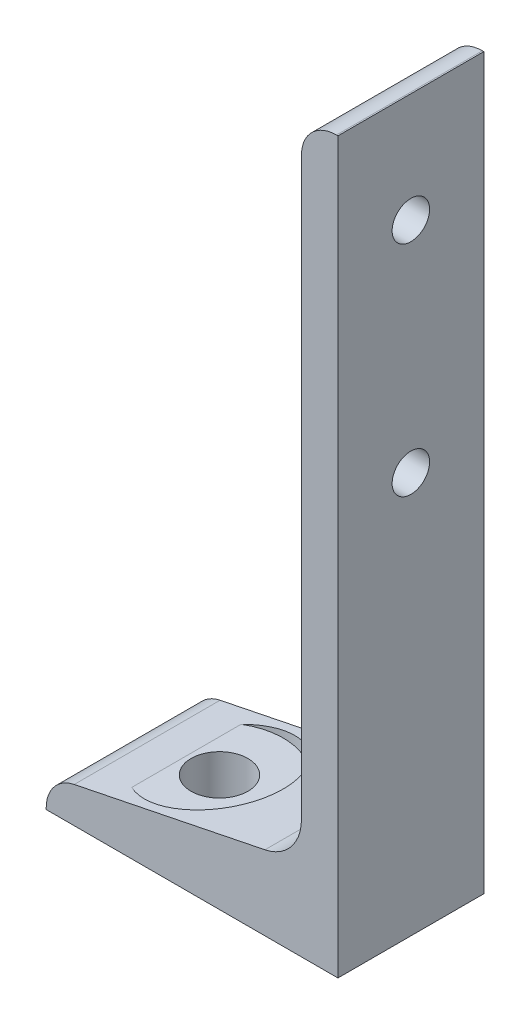
SolidWorks part; units mm, degrees
ref_plane "Front Plane" through (0, 0, 0) normal (0, 0, 1) x (1, 0, 0)
ref_plane "Top Plane" through (0, 0, 0) normal (0, 1, 0) x (1, 0, 0)
ref_plane "Right Plane" through (0, 0, 0) normal (1, 0, 0) x (0, 0, -1)
sketch "Sketch1" plane through (0, 0, 0) normal (0, 0, 1) x (1, 0, 0)
  line L0 (0, 127) -> (0, 0)
  line L1 (0, 0) -> (-50.8, 0)
  line L2 (-50.8, 0) -> (-50.8, 0.254)
  line L3 (-45.9189, 6.2277) -> (-12.7056, 12.9823)
  line L4 (-6.35, 20.7605) -> (-6.35, 120.904)
  line L5 (-0.254, 127) -> (0, 127)
  arc A0 (-50.8, 0.254) -> (-45.9189, 6.2277) centre (-44.704, 0.254) cw
  arc A1 (-6.35, 120.904) -> (-0.254, 127) centre (-0.254, 120.904) cw
  arc A2 (-12.7056, 12.9823) -> (-6.35, 20.7605) centre (-14.2875, 20.7605) ccw
  point P11 (-6.35, 127)
  point P14 (-6.35, 14.2748)
  dimension "D1" = 6.096
  dimension "D3" = 7.9375
  dimension "A" = 127
  dimension "D2" = 14.2748
  dimension "F" = 50.8
  dimension "E" = 6.35
extrude "Extrude1" add sketch "Sketch1" along normal mid plane 25.4
sketch "Sketch2" plane through (0, 0, 0) normal (1, 0, 0) x (0, 0, -1)
  line L0 (0, 0) -> (0, 69.85) construction
  line L1 (0, 69.85) -> (0, 107.95) construction
  line L2 (-12.7, 127) -> (12.7, 127) construction
  circle A0 centre (0, 69.85) radius 3.2639
  circle A1 centre (0, 107.95) radius 3.2639
  dimension "D1" = 15.7861
  dimension "K" = 6.5278
  dimension "B" = 69.85
  dimension "C" = 38.1
sketch "Sketch3" plane through (0, 0, 0) normal (0, 1, 0) x (1, 0, 0)
  line L0 (-50.8, 0) -> (-33.3248, 0) construction
  line L1 (-50.8, -12.7) -> (-50.8, 12.7) construction
  circle A0 centre (-33.3248, 0) radius 4.953
  dimension "L" = 9.906
  dimension "D1" = 17.4752
ref_plane "Plane1" through (0, 7.62, 0) normal (0, 1, 0) x (-1, 0, 0)
sketch "Sketch4" plane through (0, 7.62, 0) normal (0, 1, 0) x (-1, 0, 0)
  line L0 (33.3248, 11.1125) -> (50.8, 11.1125)
  line L1 (33.3248, -11.1125) -> (50.8, -11.1125)
  line L2 (50.8, 12.7) -> (50.8, -12.7) construction
  line L3 (50.8, 11.1125) -> (50.8, -11.1125)
  arc A0 (33.3248, 11.1125) -> (33.3248, -11.1125) centre (33.3248, 0) ccw
  arc A1 (33.3248, 11.1125) -> (33.3248, -11.1125) centre (33.3248, 0) cw construction
  dimension "M" = 22.225
sketch "Sketch5" plane through (-6.35, 0, 0) normal (-1, 0, 0) x (0, 0, 1)
  circle A0 centre (0, 69.85) radius 3.2639 construction
  circle A1 centre (0, 107.95) radius 3.2639 construction
  circle A2 centre (0, 69.85) radius 3.2639
  circle A3 centre (0, 107.95) radius 3.2639
extrude "Cut-Extrude1" cut sketch "Sketch5" against normal through all
sketch "Sketch6" plane through (0, 7.62, 0) normal (0, 1, 0) x (-1, 0, 0)
  circle A0 centre (33.3248, 0) radius 4.953 construction
  circle A1 centre (33.3248, 0) radius 4.953
extrude "Cut-Extrude2" cut sketch "Sketch6" against normal through all
sketch "Sketch7" plane through (0, 7.62, 0) normal (0, 1, 0) x (-1, 0, 0)
  line L0 (33.3248, 0) -> (33.3248, 11.1125) construction
  line L3 (50.8, 11.1125) -> (33.3248, 11.1125)
  line L4 (50.8, 11.1125) -> (33.3248, 11.1125) construction
  line L5 (50.8, -11.1125) -> (50.8, 11.1125)
  line L6 (50.8, -11.1125) -> (50.8, 11.1125) construction
  line L7 (33.3248, -11.1125) -> (50.8, -11.1125)
  line L8 (33.3248, -11.1125) -> (50.8, -11.1125) construction
  arc A1 (33.3248, 11.1125) -> (33.3248, -11.1125) centre (33.3248, 0) ccw
  circle A2 centre (33.3248, 0) radius 11.1125
  dimension "D1" = 0
extrude "Cut-Extrude3" cut sketch "Sketch7" along normal through all
sketch "Sketch9" plane through (-6.35, 0, 0) normal (-1, 0, 0) x (0, 0, 1)
  line L0 (-6.35, 107.95) -> (6.35, 107.95) construction
  circle A0 centre (6.35, 107.95) radius 3.2639
  circle A1 centre (6.35, 69.85) radius 3.2639
  circle A2 centre (-6.35, 69.85) radius 3.2639
  circle A3 centre (-6.35, 107.95) radius 3.2639
  circle A4 centre (0, 69.85) radius 3.2639 construction
  dimension "D1" = 12.7
sketch "Sketch10" plane through (0, 0, 0) normal (0, 1, 0) x (1, 0, 0)
  line L0 (-33.3248, -6.35) -> (-33.3248, 6.35) construction
  line L1 (-50.8, -11.1125) -> (-50.8, 11.1125) construction
  line L2 (-50.8, 17.4625) -> (-33.3248, 17.4625)
  line L3 (-50.8, 17.4625) -> (-50.8, -4.7625)
  line L4 (-50.8, -4.7625) -> (-33.3248, -4.7625)
  line L6 (-50.8, 4.7625) -> (-33.3248, 4.7625)
  line L7 (-50.8, 4.7625) -> (-50.8, -17.4625)
  line L8 (-50.8, -17.4625) -> (-33.3248, -17.4625)
  circle A0 centre (-33.3248, 6.35) radius 4.953
  circle A1 centre (-33.3248, -6.35) radius 4.953
  circle A2 centre (-33.3248, 0) radius 4.953 construction
  arc A3 (-33.3248, -4.7625) -> (-33.3248, 17.4625) centre (-33.3248, 6.35) ccw
  arc A4 (-33.3248, -17.4625) -> (-33.3248, 4.7625) centre (-33.3248, -6.35) ccw
  dimension "D1" = 12.7
sketch "Sketch11" [suppressed] plane through (0, 6.858, 0) normal (0, 1, 0) x (-1, 0, 0)
  line L3 (33.3248, -33.3375) -> (50.8, -33.3375)
  line L4 (50.8, -4.7625) -> (33.3248, -4.7625)
  line L5 (50.8, -33.3375) -> (50.8, -4.7625)
  line L6 (33.3248, -33.3375) -> (50.8, -33.3375)
  line L7 (50.8, -4.7625) -> (33.3248, -4.7625)
  line L8 (50.8, -33.3375) -> (50.8, -4.7625)
  line L9 (33.3248, 4.7625) -> (50.8, 4.7625)
  line L10 (50.8, 4.7625) -> (50.8, 33.3375)
  line L11 (50.8, 33.3375) -> (33.3248, 33.3375)
  line L12 (33.3248, 4.7625) -> (50.8, 4.7625)
  line L13 (50.8, 4.7625) -> (50.8, 33.3375)
  line L14 (50.8, 33.3375) -> (33.3248, 33.3375)
  arc A5 (33.3248, -4.7625) -> (33.3248, -33.3375) centre (33.3248, -19.05) ccw
  arc A6 (33.3248, -4.7625) -> (33.3248, -33.3375) centre (33.3248, -19.05) ccw
  arc A7 (33.3248, 33.3375) -> (33.3248, 4.7625) centre (33.3248, 19.05) ccw
  arc A8 (33.3248, 33.3375) -> (33.3248, 4.7625) centre (33.3248, 19.05) ccw
  dimension "D3" = 0
  dimension "D4" = 0
extrude "Cut-Extrude4" [suppressed] cut sketch "Sketch11" along normal through all
sketch "Sketch12" [suppressed] plane through (0, 6.858, 0) normal (0, 1, 0) x (-1, 0, 0)
  circle A0 centre (33.3248, 19.05) radius 6.7437 construction
  circle A1 centre (33.3248, -19.05) radius 6.7437 construction
  circle A2 centre (33.3248, 19.05) radius 6.7437
  circle A3 centre (33.3248, -19.05) radius 6.7437
extrude "Cut-Extrude5" [suppressed] cut sketch "Sketch12" against normal through all
sketch "Sketch13" [suppressed] plane through (-6.35, 0, 0) normal (-1, 0, 0) x (0, 0, 1)
  circle A0 centre (-19.05, 69.85) radius 4.1656 construction
  circle A1 centre (-19.05, 107.95) radius 4.1656 construction
  circle A2 centre (19.05, 107.95) radius 4.1656 construction
  circle A3 centre (19.05, 69.85) radius 4.1656 construction
  circle A4 centre (-19.05, 69.85) radius 4.1656
  circle A5 centre (-19.05, 107.95) radius 4.1656
  circle A6 centre (19.05, 107.95) radius 4.1656
  circle A7 centre (19.05, 69.85) radius 4.1656
extrude "Cut-Extrude6" [suppressed] cut sketch "Sketch13" against normal through all
equation "\"D1@Sketch9\" = \"J@Extrude1\"/2"
equation "\"D1@Sketch10\" = \"J@Extrude1\"/2"
